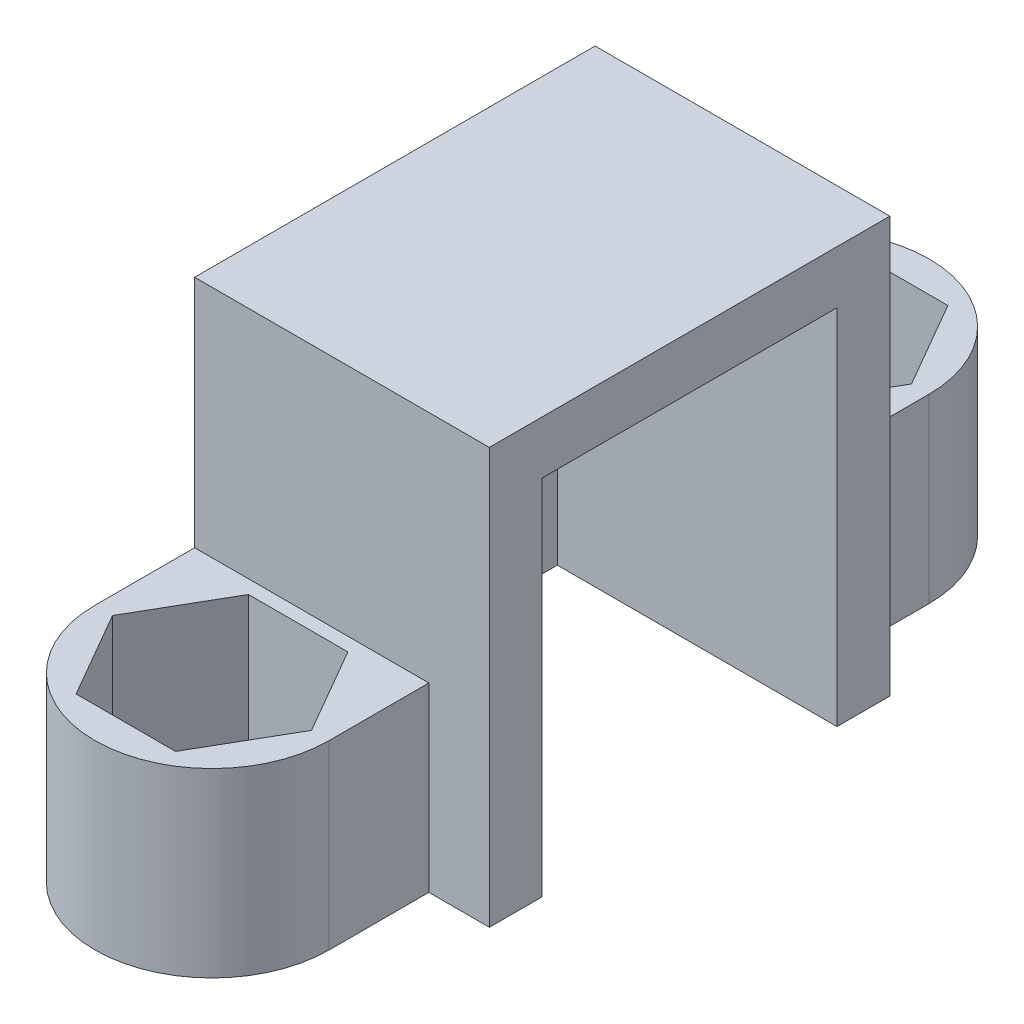
SolidWorks part; units mm, degrees
ref_plane "Přední rovina" through (0, 0, 0) normal (0, 0, 1) x (1, 0, 0)
ref_plane "Horní rovina" through (0, 0, 0) normal (0, 1, 0) x (1, 0, 0)
ref_plane "Pravá rovina" through (0, 0, 0) normal (1, 0, 0) x (0, 0, -1)
sketch "Sketch1" plane through (0, 0, 0) normal (1, 0, 0) x (0, 0, -1)
  line L0 (-4.875, 5.125) -> (-4.875, -6.875)
  line L1 (-6.625, 6.875) -> (6.625, 6.875)
  line L2 (-6.625, 6.875) -> (-6.625, -6.875)
  line L3 (-6.625, -6.875) -> (6.625, -6.875)
  line L4 (6.625, 6.875) -> (6.625, -6.875)
  line L5 (-6.625, 6.875) -> (6.625, -6.875) construction
  line L6 (-6.625, -6.875) -> (6.625, 6.875) construction
  line L7 (-4.875, 5.125) -> (4.875, 5.125)
  line L8 (4.875, 5.125) -> (4.875, -6.875)
  point P0 (0, 0)
  dimension "D1" = 1.75
  dimension "D2" = 1.75
  dimension "D3" = 1.75
  dimension "D4" = 9.75
  dimension "D5" = 12
extrude "Boss-Extrude1" add sketch "Sketch1" along normal blind 9.75 contours L7 L8 L3 L4 L1 L2 L0
sketch "Sketch2" plane through (0, -6.875, 0) normal (0, -1, 0) x (1, 0, 0)
  line L0 (3.875, 1.9293) -> (3.875, 9.925) construction
  line L1 (0, 1.9293) -> (0, 9.925)
  line L4 (9.75, 4.875) -> (0, 4.875) construction
  line L5 (7.75, 1.9293) -> (7.75, 9.925)
  line L6 (9.75, 6.625) -> (0, 6.625) construction
  line L7 (9.75, 4.875) -> (0, 4.875)
  line L8 (2.2296, 12.775) -> (0.5841, 9.925)
  line L9 (0.5841, 9.925) -> (2.2296, 7.075)
  line L10 (2.2296, 7.075) -> (5.5204, 7.075)
  line L11 (5.5204, 7.075) -> (7.1659, 9.925)
  line L12 (7.1659, 9.925) -> (5.5204, 12.775)
  line L13 (5.5204, 12.775) -> (2.2296, 12.775)
  line L14 (0, 6.625) -> (0, -6.625) construction
  circle A3 centre (3.875, 9.925) radius 2.85 construction
  arc A4 (0, 1.9293) -> (7.75, 1.9293) centre (3.875, 1.9293) ccw
  arc A5 (7.75, 9.925) -> (0, 9.925) centre (3.875, 9.925) ccw
  point P1 (3.875, 5.9271)
  dimension "D1" = 5.7
  dimension "D3" = 3.3
  dimension "D2" = 7.75
extrude "Boss-Extrude2" add sketch "Sketch2" against normal blind 5 from offset 1 offset against normal yes
sketch "Sketch3" plane through (0, -5.875, 0) normal (0, -1, 0) x (1, 0, 0)
  line L6 (7.75, 6.625) -> (7.75, 9.925) construction
  line L7 (0, 6.625) -> (0, 9.925) construction
  line L8 (7.75, 6.625) -> (7.75, 9.925)
  line L9 (0, 6.625) -> (0, 9.925)
  line L10 (7.75, 6.625) -> (0, 6.625)
  circle A2 centre (3.875, 9.925) radius 1.6
  arc A3 (7.75, 9.925) -> (0, 9.925) centre (3.875, 9.925) ccw construction
  arc A4 (7.75, 9.925) -> (0, 9.925) centre (3.875, 9.925) ccw
  dimension "D1" = 3.2
extrude "Boss-Extrude3" add sketch "Sketch3" along normal up to surface (1 mm away) up to face at (4.875, -6.875, 5.75)
mirror "Mirror1" about plane through (0, 0, 0) normal (0, 0, 1) of "Boss-Extrude3", "Boss-Extrude2"
sketch "Sketch4" plane through (0, 0, 0) normal (-1, 0, 0) x (0, 0, 1)
  line L0 (-6.625, 6.875) -> (-6.625, -6.875)
  line L1 (-4.875, -6.875) -> (-9.925, -6.875) construction
  line L2 (-6.625, -6.875) -> (-4.375, -6.875)
  line L3 (-4.375, -6.875) -> (-4.375, 4.625)
  line L4 (-4.375, 4.625) -> (4.375, 4.625)
  line L5 (4.375, 4.625) -> (4.375, -6.875)
  line L6 (4.375, -6.875) -> (6.625, -6.875)
  line L7 (9.925, -6.875) -> (4.875, -6.875) construction
  line L8 (6.625, -6.875) -> (6.625, 6.875)
  line L9 (6.625, 6.875) -> (-6.625, 6.875)
  line L10 (6.625, 6.875) -> (6.625, -0.875) construction
  line L11 (4.875, 5.125) -> (4.875, -6.875) construction
  line L12 (4.875, 5.125) -> (-4.875, 5.125) construction
  line L13 (-4.875, 5.125) -> (-4.875, -6.875) construction
  dimension "D1" = 0.5
  dimension "D2" = 0.5
  dimension "D3" = 0.5
extrude "Boss-Extrude4" add sketch "Sketch4" against normal blind 0.5
